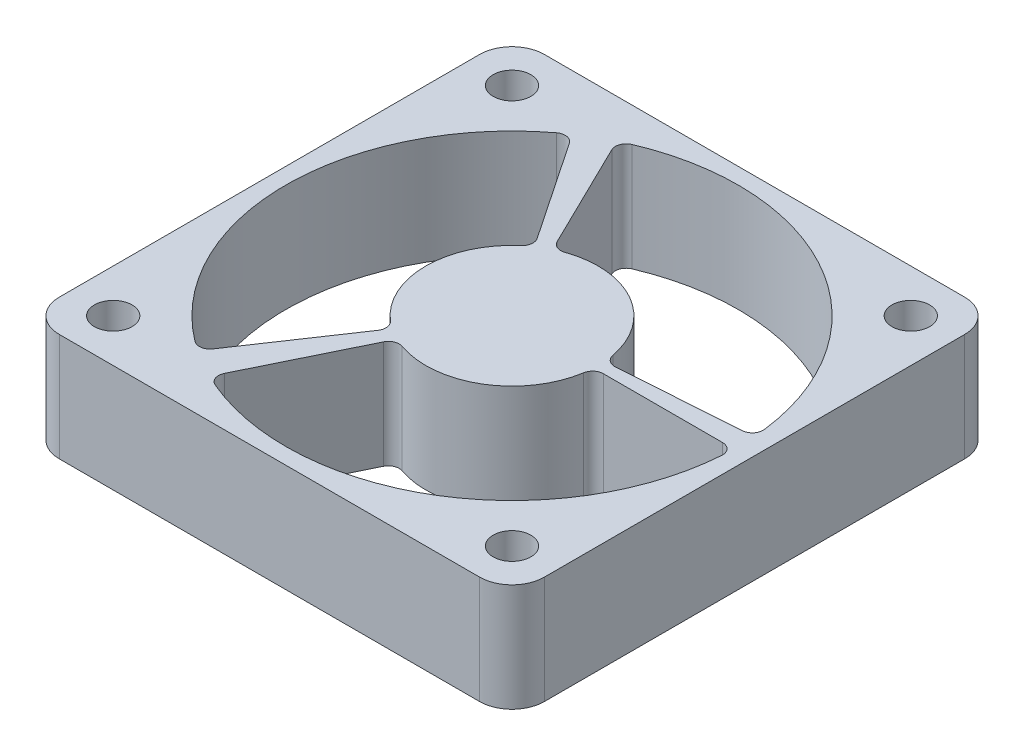
SolidWorks part; units mm, degrees
ref_plane "Płaszczyzna przednia" through (0, 0, 0) normal (0, 0, 1) x (1, 0, 0)
ref_plane "Płaszczyzna górna" through (0, 0, 0) normal (0, 1, 0) x (1, 0, 0)
ref_plane "Płaszczyzna prawa" through (0, 0, 0) normal (1, 0, 0) x (0, 0, -1)
sketch "Szkic1" plane through (0, 0, 0) normal (0, 1, 0) x (1, 0, 0)
  line L1 (19.5, -22.5) -> (-19.5, -22.5)
  line L2 (22.5, -19.5) -> (22.5, 19.5)
  line L3 (19.5, 22.5) -> (-19.5, 22.5)
  line L4 (-22.5, -19.5) -> (-22.5, 19.5)
  line L5 (22.5, -22.5) -> (-22.5, 22.5) construction
  line L6 (22.5, 22.5) -> (-22.5, -22.5) construction
  arc A0 (-19.5, -22.5) -> (-22.5, -19.5) centre (-19.5, -19.5) cw
  arc A1 (19.5, -22.5) -> (22.5, -19.5) centre (19.5, -19.5) ccw
  arc A2 (22.5, 19.5) -> (19.5, 22.5) centre (19.5, 19.5) ccw
  arc A3 (-22.5, 19.5) -> (-19.5, 22.5) centre (-19.5, 19.5) cw
  point P0 (0, 0)
  dimension "D3" = 3
  dimension "D1" = 45
  dimension "D2" = 45
extrude "Dodanie-wyciągnięcie1" add sketch "Szkic1" along normal blind 10
sketch "Szkic2" plane through (0, 10, 0) normal (0, 1, 0) x (1, 0, 0)
  line L0 (19.9498, -0.4161) -> (8.8879, -0.4161)
  line L1 (-22.5, 19.5) -> (-22.5, -19.5) construction
  line L2 (19.5, 22.5) -> (-19.5, 22.5) construction
  line L3 (19.9188, 1.4498) -> (8.9101, 0.6868)
  line L10 (-8.7129, -17.971) -> (-3.8667, -8.0573)
  line L11 (-11.2069, -16.5311) -> (-5.0444, -7.3773)
  line L12 (-11.2069, 16.5311) -> (-5.0444, 7.3773)
  line L13 (-8.7129, 17.971) -> (-3.8667, 8.0573)
  circle A0 centre (-18.5, 18.5) radius 1.75
  circle A1 centre (18.5, 18.5) radius 1.75
  circle A2 centre (18.5, -18.5) radius 1.75
  circle A3 centre (-18.5, -18.5) radius 1.75
  arc A5 (-8.2052, -19.3307) -> (20.9473, -1.4869) centre (0, 0) ccw
  arc A6 (20.8422, 2.5698) -> (-8.2052, 19.3307) centre (0, 0) ccw
  arc A7 (-5.2213, 6.0612) -> (-5.2213, -6.0612) centre (0, 0) ccw
  arc A8 (-12.6382, 16.7713) -> (-12.6382, -16.7713) centre (0, 0) ccw
  arc A9 (-2.6385, -7.5524) -> (7.9004, -1.2587) centre (0, 0) ccw
  arc A10 (7.8586, 1.4973) -> (-2.6385, 7.5524) centre (0, 0) ccw
  arc A11 (-11.2069, 16.5311) -> (-12.6382, 16.7713) centre (-12.0364, 15.9726) ccw
  arc A12 (-12.6382, -16.7713) -> (-11.2069, -16.5311) centre (-12.0364, -15.9726) ccw
  arc A13 (-5.0444, -7.3773) -> (-5.2213, -6.0612) centre (-5.874, -6.8188) ccw
  arc A14 (-5.2213, 6.0612) -> (-5.0444, 7.3773) centre (-5.874, 6.8188) ccw
  arc A15 (-8.7129, -17.971) -> (-8.2052, -19.3307) centre (-7.8145, -18.4102) ccw
  arc A16 (-8.7129, 17.971) -> (-8.2052, 19.3307) centre (-7.8145, 18.4102) cw
  arc A17 (19.9188, 1.4498) -> (20.8422, 2.5698) centre (19.8497, 2.4475) ccw
  arc A18 (7.8586, 1.4973) -> (8.9101, 0.6868) centre (8.841, 1.6844) ccw
  arc A19 (-3.8667, 8.0573) -> (-2.6385, 7.5524) centre (-2.9683, 8.4964) ccw
  arc A20 (-3.8667, -8.0573) -> (-2.6385, -7.5524) centre (-2.9683, -8.4964) cw
  arc A21 (20.9473, -1.4869) -> (19.9498, -0.4161) centre (19.9498, -1.4161) ccw
  arc A22 (8.8879, -0.4161) -> (7.9004, -1.2587) centre (8.8879, -1.4161) ccw
  dimension "D1" = 4
  dimension "D3" = 1
  dimension "D4" = 1
  dimension "D5" = 3.5
  dimension "D8" = 21
  dimension "D9" = 8
  dimension "D2" = 4
  dimension "D6" = 37
  dimension "D7" = 37
extrude "Wytnij-wyciągnięcie1" cut sketch "Szkic2" against normal blind 10
